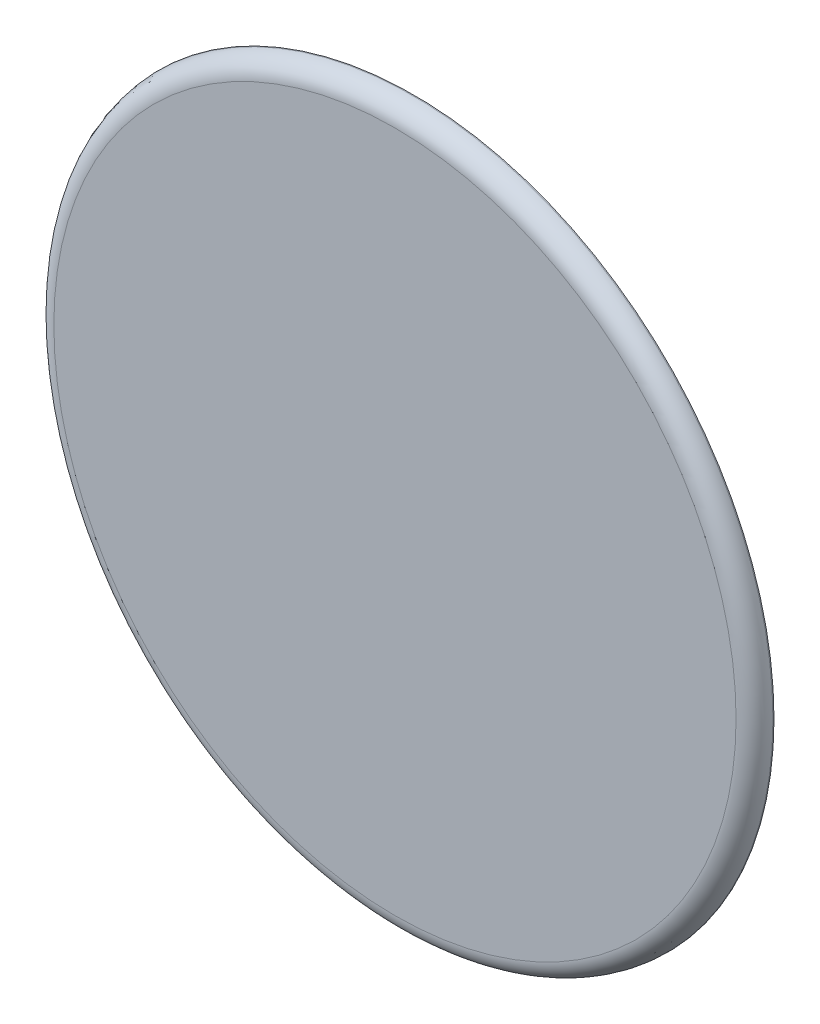
SolidWorks part; units mm, degrees
ref_plane "Front" through (0, 0, 0) normal (0, 0, 1) x (1, 0, 0)
ref_plane "Top" through (0, 0, 0) normal (0, 1, 0) x (1, 0, 0)
ref_plane "Right" through (0, 0, 0) normal (1, 0, 0) x (0, 0, -1)
sketch "Sketch1" plane through (0, 0, 0) normal (0, 0, 1) x (1, 0, 0)
  circle A0 centre (0, 0) radius 190
  dimension "D1" = 380
extrude "Boss-Extrude1" add sketch "Sketch1" along normal blind 10 draft 3
fillet "Fillet1" radius 10 1 edges at (189.4759, 0, 10)
